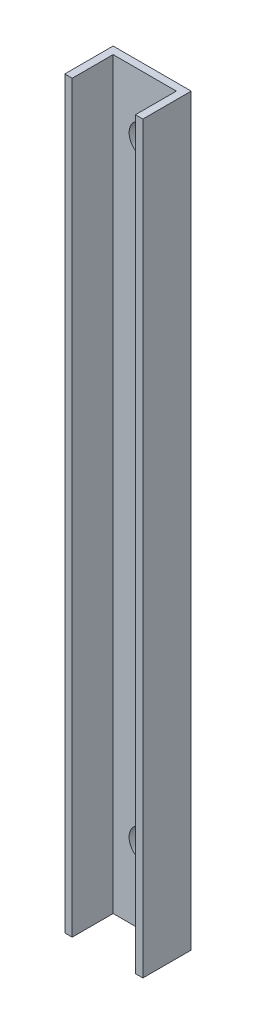
SolidWorks part; units mm, degrees
ref_plane "Front Plane" through (0, 0, 0) normal (0, 0, 1) x (1, 0, 0)
ref_plane "Top Plane" through (0, 0, 0) normal (0, 1, 0) x (1, 0, 0)
ref_plane "Right Plane" through (0, 0, 0) normal (1, 0, 0) x (0, 0, -1)
sketch "Sketch1" plane through (0, 0, 0) normal (0, 1, 0) x (1, 0, 0)
  line L0 (-3.47, -1.8133) -> (-3.47, 4.6867)
  line L1 (-3.47, 4.6867) -> (7.03, 4.6867)
  line L2 (7.03, 4.6867) -> (7.03, -1.8133)
  dimension "D1" = 10.5
  dimension "D2" = 6.5
  dimension "D3" = 6.5
extrude "Extrude-Thin1" add sketch "Sketch1" along normal blind 100 thin
sketch "Sketch2" plane through (0, 0, -4.6867) normal (0, 0, -1) x (-1, 0, 0)
  line L0 (3.47, 0) -> (-7.03, 0) construction
  line L2 (3.47, 100) -> (3.47, 0) construction
  circle A0 centre (-1.78, 92) radius 2.1
  circle A1 centre (-1.78, 10) radius 2.1
  dimension "D1" = 92
  dimension "D2" = 5.25
  dimension "D3" = 5.25
  dimension "D4" = 4.2
  dimension "D5" = 82
extrude "Cut-Extrude1" cut sketch "Sketch2" against normal blind 10
